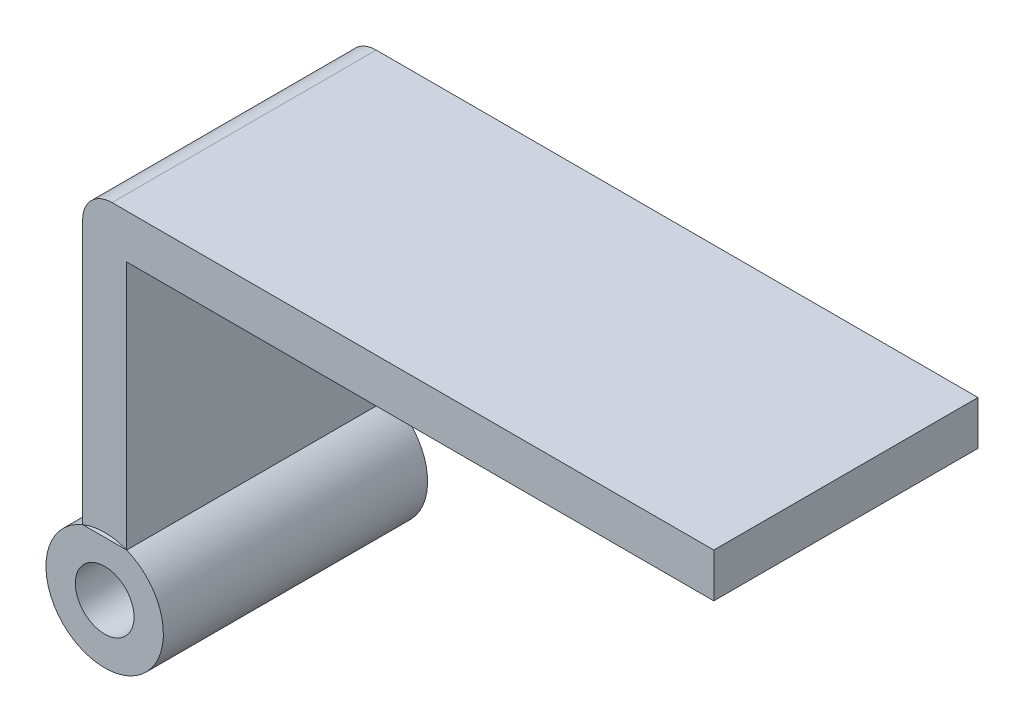
SolidWorks part; units mm, degrees
ref_plane "Front Plane" through (0, 0, 0) normal (0, 0, 1) x (1, 0, 0)
ref_plane "Top Plane" through (0, 0, 0) normal (0, 1, 0) x (1, 0, 0)
ref_plane "Right Plane" through (0, 0, 0) normal (1, 0, 0) x (0, 0, -1)
sketch "Sketch1" plane through (0, 0, 0) normal (0, 0, 1) x (1, 0, 0)
  line L2 (-1.5, 21.9186) -> (1.5, 21.9186)
  line L7 (-1.5, 30.3964) -> (1.5, 30.3964)
  line L8 (-1.5, 30.3964) -> (-1.5, 50.3964)
  line L9 (-1.5, 50.3964) -> (1.5, 50.3964)
  line L10 (1.5, 30.3964) -> (1.5, 47.3964)
  line L12 (-1.5, 50.3964) -> (41.5, 50.3964)
  line L13 (-1.5, 50.3964) -> (-1.5, 57.3964)
  line L14 (1.5, 47.3964) -> (41.5, 47.3964)
  line L15 (41.5, 50.3964) -> (41.5, 47.3964)
  circle A0 centre (0, 26.6883) radius 4
  circle A4 centre (0, 26.6883) radius 2
  point P11 (0, 30.3964)
  dimension "D3" = 8
  dimension "D4" = 3
  dimension "D5" = 20
  dimension "D6" = 40
  dimension "D7" = 3
extrude "Boss-Extrude1" add sketch "Sketch1" along normal blind 18 contours A0 L10 L14 L15 L12 L9 L8 | L7 A0 A4
fillet "Fillet1" radius 2 1 edges at (-1.5, 50.3964, 9)
